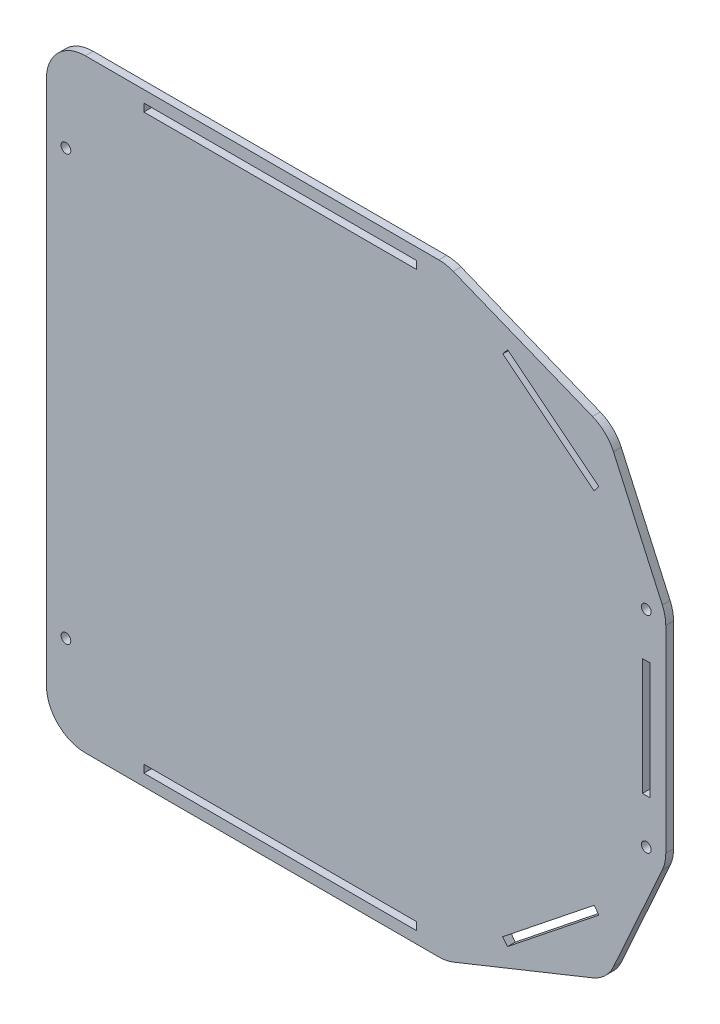
SolidWorks part; units mm, degrees
material "PVC rigido"
ref_plane "Piano frontale" through (0, 0, 0) normal (0, 0, 1) x (1, 0, 0)
ref_plane "Piano superiore" through (0, 0, 0) normal (0, 1, 0) x (1, 0, 0)
ref_plane "Piano destro" through (0, 0, 0) normal (1, 0, 0) x (0, 0, -1)
sketch "Schizzo1" plane through (0, 0, 0) normal (0, 0, 1) x (1, 0, 0)
  line L0 (11.6578, -77.5) -> (52.9212, -60.9097)
  line L1 (-91, -77.5) -> (11.6578, -77.5)
  line L2 (-91, -77.5) -> (-91, 77.5)
  line L3 (-91, 77.5) -> (11.6578, 77.5)
  line L4 (68, -27.5) -> (68, 27.5)
  line L5 (59.2392, 67.1366) -> (75.1147, 31.9616) construction
  line L6 (52.9212, -60.9097) -> (52.9212, 60.9097) construction
  line L7 (52.9212, -60.9097) -> (68, -27.5)
  line L8 (11.6578, 77.5) -> (52.9212, 60.9097)
  line L9 (52.9212, 60.9097) -> (68, 27.5)
  line L10 (11.6578, 77.5) -> (68, 77.5) construction
  line L11 (68, 77.5) -> (68, 27.5) construction
  line L12 (11.6578, -77.5) -> (68, -77.5) construction
  line L13 (68, -77.5) -> (68, -27.5) construction
  line L14 (53.8549, -72.3011) -> (17.8474, -86.7782) construction
  line L15 (75.1147, -31.9616) -> (59.2392, -67.1366) construction
  line L16 (17.8474, 86.7782) -> (53.8549, 72.3011) construction
  line L17 (0, 0) -> (11.6578, 77.5) construction
  line L18 (0, 0) -> (11.6578, -77.5) construction
  line L19 (11.6578, -77.5) -> (11.6578, 77.5) construction
  line L20 (-91, -77.5) -> (0, 0) construction
  line L21 (0, 0) -> (-91, 77.5) construction
  line L22 (0, 0) -> (-91, 0) construction
  line L23 (0, 0) -> (0, 77.5) construction
  point P0 (0, 0)
  dimension "D1" = 155
  dimension "D2" = 91
  dimension "D3" = 55
  dimension "D4" = 68
extrude "Estrusione-Estrusione1" add sketch "Schizzo1" along normal blind 2
hole_wizard "Foro filettato M3x0.5-1" positions "Schizzo3" profile "Schizzo2" tap size "M3x0.5" standard "Ansi Metric" end condition through all
sketch "Schizzo3" plane through (0, 0, 0) normal (0, 0, -1) x (-1, 0, 0)
  line L0 (86, -77.5) -> (86, -54.5) construction
  line L1 (91, -77.5) -> (-11.6578, -77.5) construction
  line L2 (86, -54.5) -> (86, 54.5) construction
  line L3 (86, 54.5) -> (86, 77.5) construction
  line L4 (-11.6578, 77.5) -> (91, 77.5) construction
  line L6 (0, 0) -> (86, 0) construction
  point P0 (86, -54.5)
  point P2 (86, 54.5)
sketch "Schizzo2" plane through (-86, -54.5, 0) normal (1, 0, 0) x (0, 1, 0)
  line L0 (0, 0) -> (0, 2)
  line L1 (0, 2) -> (1.25, 2)
  line L2 (1.25, 2) -> (1.25, 0)
  line L5 (1.25, 0) -> (0, 0)
  line L11 (0, -6.35) -> (0, 107.95) construction
  dimension "Thru Tap Drill Dia." = 2.5
  dimension "Thru Tap Drill Depth" = 2
cosmetic thread "Filettatura del foro1" parameters "D2"=3
cosmetic thread "Filettatura del foro2" parameters "D2"=3
sketch "Schizzo4" plane through (0, 0, 0) normal (0, 0, -1) x (-1, 0, 0)
  line L0 (31, -72.5) -> (31, 72.5) construction
  line L1 (66, -74.5) -> (-4, -74.5)
  line L2 (66, -74.5) -> (66, -72.5)
  line L3 (66, -72.5) -> (-4, -72.5)
  line L4 (-4, -74.5) -> (-4, -72.5)
  line L5 (66, 72.5) -> (-4, 72.5)
  line L6 (66, 72.5) -> (66, 74.5)
  line L7 (66, 74.5) -> (-4, 74.5)
  line L8 (-4, 72.5) -> (-4, 74.5)
  line L9 (31, 0) -> (91, 0) construction
  line L10 (91, 77.5) -> (91, -77.5) construction
  line L11 (91, -77.5) -> (-11.6578, -77.5) construction
  dimension "D1" = 2
  dimension "D2" = 3
  dimension "D3" = 70
  dimension "D4" = 60
extrude "Taglio-Estrusione1" cut sketch "Schizzo4" against normal blind 10
hole_wizard "Foro filettato M3x0.5-2" positions "Schizzo6" profile "Schizzo5" tap size "M3x0.5" standard "Ansi Metric" end condition through all
sketch "Schizzo6" plane through (0, 0, 2) normal (0, 0, 1) x (1, 0, 0)
  line L16 (48.3639, -58.8529) -> (63, -26.4239)
  line L17 (63, -26.4239) -> (63, 26.4239)
  line L18 (63, 26.4239) -> (48.3639, 58.8529)
  line L19 (48.3639, -58.8529) -> (63, -26.4239) construction
  line L20 (63, -26.4239) -> (63, 26.4239) construction
  line L21 (63, 26.4239) -> (48.3639, 58.8529) construction
  point P0 (63, 26.4239)
  point P2 (63, -26.4239)
  dimension "D1" = 5
sketch "Schizzo5" plane through (63, 26.4239, 2) normal (1, 0, 0) x (0, -1, 0)
  line L0 (0, 0) -> (0, 2)
  line L1 (0, 2) -> (1.25, 2)
  line L2 (1.25, 2) -> (1.25, 0)
  line L5 (1.25, 0) -> (0, 0)
  line L11 (0, -6.35) -> (0, 107.95) construction
  dimension "Thru Tap Drill Dia." = 2.5
  dimension "Thru Tap Drill Depth" = 2
cosmetic thread "Filettatura del foro3" parameters "D2"=3
cosmetic thread "Filettatura del foro4" parameters "D2"=3
sketch "Schizzo7" plane through (0, 0, 2) normal (0, 0, 1) x (1, 0, 0)
  line L0 (27.3882, 66.3524) -> (50.8383, 47.6416)
  line L1 (49.5909, 46.0783) -> (26.1408, 64.7891)
  line L2 (26.1408, 64.7891) -> (27.3882, 66.3524)
  line L3 (49.5909, 46.0783) -> (50.8383, 47.6416)
  line L4 (63, 26.4239) -> (4, 73.5) construction
  line L5 (4, 74.5) -> (4, 72.5) construction
  line L6 (4, 74.5) -> (4, 72.5) construction
  line L7 (26.7645, 65.5707) -> (50.2146, 46.8599) construction
  line L8 (38.4895, 56.2153) -> (33.5, 49.962) construction
  line L9 (63, 26.4239) -> (63, 15) construction
  line L10 (63, 15) -> (63, -15) construction
  line L11 (63, -15) -> (63, -26.4239) construction
  line L12 (63, -26.4239) -> (4, -73.5) construction
  line L15 (4, -72.5) -> (4, -74.5) construction
  line L16 (49.5909, -46.0783) -> (26.1408, -64.7891)
  line L17 (26.1408, -64.7891) -> (27.3882, -66.3524)
  line L18 (27.3882, -66.3524) -> (50.8383, -47.6416)
  line L19 (50.8383, -47.6416) -> (49.5909, -46.0783)
  line L20 (50.2146, -46.8599) -> (26.7645, -65.5707) construction
  line L21 (33.5, -49.962) -> (38.4895, -56.2153) construction
  line L23 (64, -15) -> (62, -15)
  line L24 (64, -15) -> (64, 15)
  line L25 (64, 15) -> (62, 15)
  line L26 (62, -15) -> (62, 15)
  dimension "D1" = 30
  dimension "D2" = 8
  dimension "D3" = 30
extrude "Taglio-Estrusione2" cut sketch "Schizzo7" against normal blind 10
fillet "Raccordo1" radius 10 2 edges at (-91, 77.5, 1) (-91, -77.5, 1)
fillet "Raccordo2" radius 10 6 edges at (11.6578, -77.5, 1) (52.9212, -60.9097, 1) (68, -27.5, 1) (68, 27.5, 1) (52.9212, 60.9097, 1) (11.6578, 77.5, 1)
